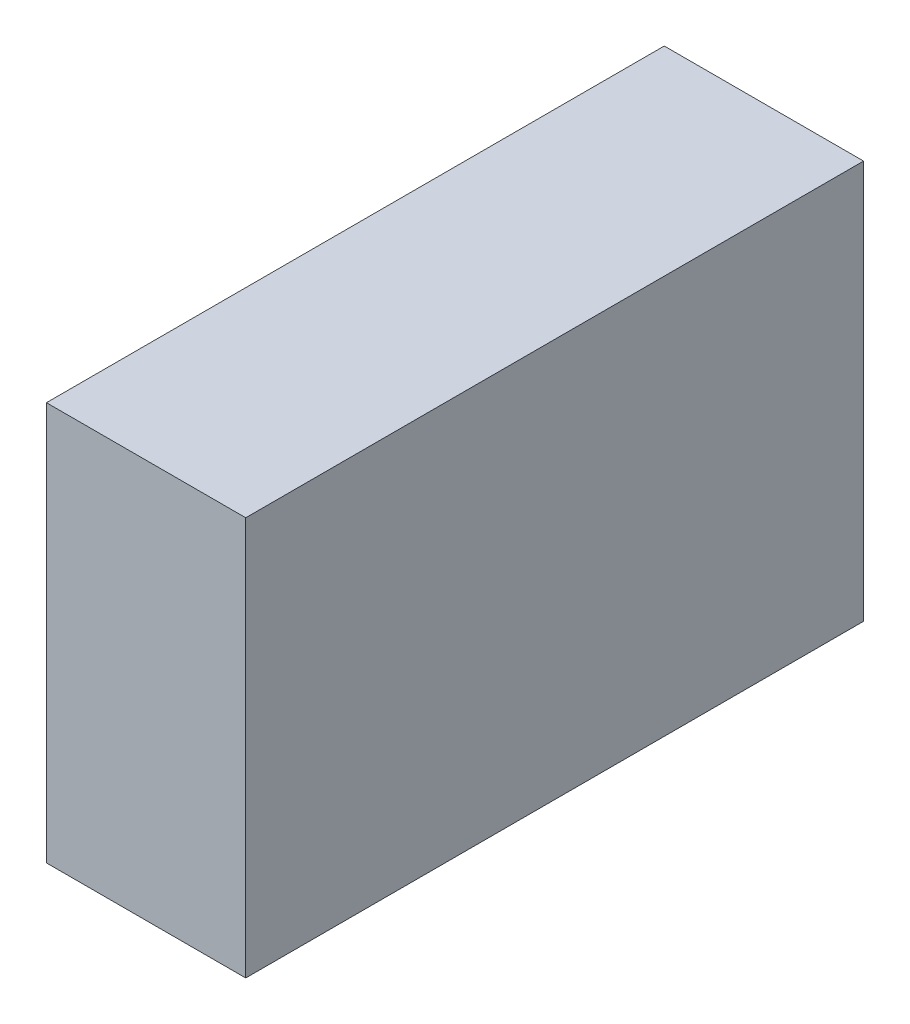
SolidWorks part; units mm, degrees
ref_plane "Front Plane" through (0, 0, 0) normal (0, 0, 1) x (1, 0, 0)
ref_plane "Top Plane" through (0, 0, 0) normal (0, 1, 0) x (1, 0, 0)
ref_plane "Right Plane" through (0, 0, 0) normal (1, 0, 0) x (0, 0, -1)
sketch "Sketch1" plane through (0, 0, 0) normal (1, 0, 0) x (0, 0, -1)
  line L1 (0, 0) -> (31, 0)
  line L2 (0, 0) -> (0, 20)
  line L3 (0, 20) -> (31, 20)
  line L4 (31, 0) -> (31, 20)
extrude "Boss-Extrude1" add sketch "Sketch1" along normal blind 10
